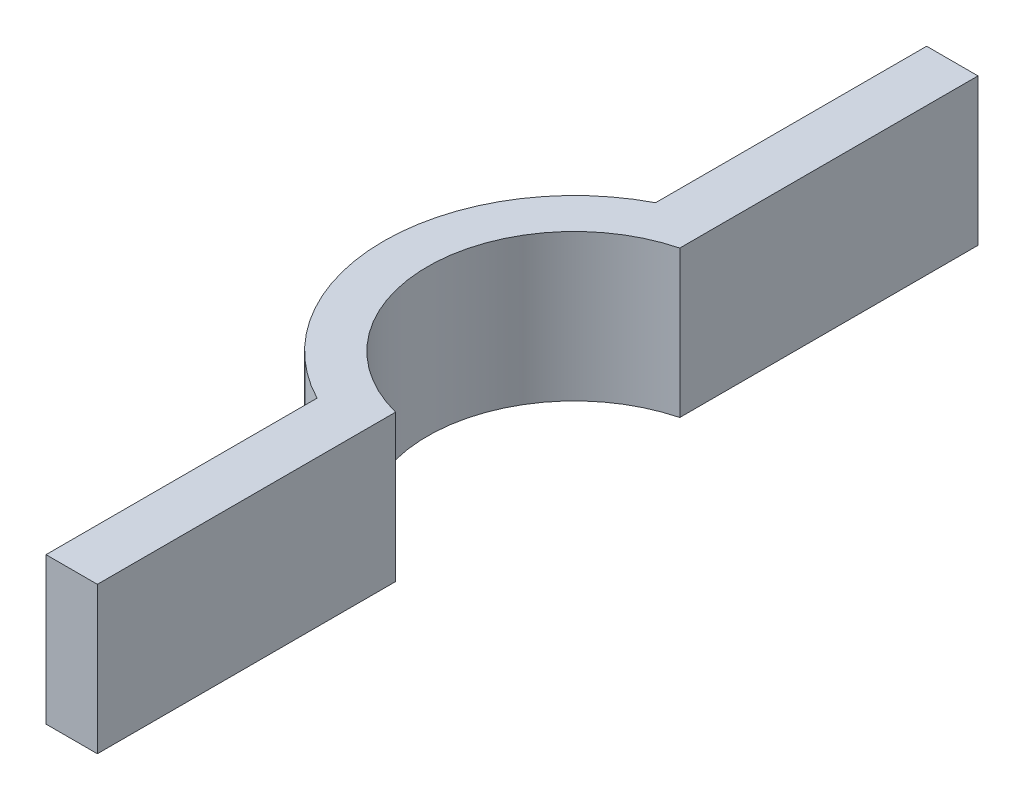
SolidWorks part; units mm, degrees
ref_plane "前视基准面" through (0, 0, 0) normal (0, 0, 1) x (1, 0, 0)
ref_plane "上视基准面" through (0, 0, 0) normal (0, 1, 0) x (1, 0, 0)
ref_plane "右视基准面" through (0, 0, 0) normal (1, 0, 0) x (0, 0, -1)
other "Configuration Table"
sketch "草图1" plane through (0, 0, 0) normal (0, 1, 0) x (1, 0, 0)
  circle A0 centre (0, 0) radius 13
  dimension "D1" = 26
extrude "凸台-拉伸1" add sketch "草图1" along normal blind 10
sketch "草图2" plane through (0, 10, 0) normal (0, 1, 0) x (1, 0, 0)
  line L0 (0, 0) -> (0, 13) construction
  line L1 (0, 0) -> (0, -13) construction
  line L3 (-6, 30) -> (6, 30)
  line L4 (-6, 30) -> (-6, -30)
  line L5 (-6, -30) -> (6, -30)
  line L6 (6, 30) -> (6, -30)
  circle A0 centre (0, 0) radius 13 construction
  dimension "D1" = 12
  dimension "D2" = 6
  dimension "D3" = 60
  dimension "D4" = 30
extrude "凸台-拉伸2" add sketch "草图2" against normal blind 10
sketch "草图3" plane through (0, 10, 0) normal (0, 1, 0) x (1, 0, 0)
  circle A0 centre (0, 0) radius 10
  dimension "D1" = 20
extrude "切除-拉伸1" cut sketch "草图3" against normal blind 10
sketch "草图4" plane through (0, 10, 0) normal (0, 1, 0) x (1, 0, 0)
  line L0 (0, 30) -> (0, 24.413) construction
  line L1 (-2.5, 30) -> (30.1881, 30)
  line L2 (-2.5, 30) -> (-2.5, -31.5796)
  line L3 (-2.5, -31.5796) -> (30.1881, -31.5796)
  line L4 (30.1881, 30) -> (30.1881, -31.5796)
  line L5 (6, 30) -> (-6, 30) construction
  dimension "D1" = 2.5
extrude "切除-拉伸2" cut sketch "草图4" against normal blind 10
